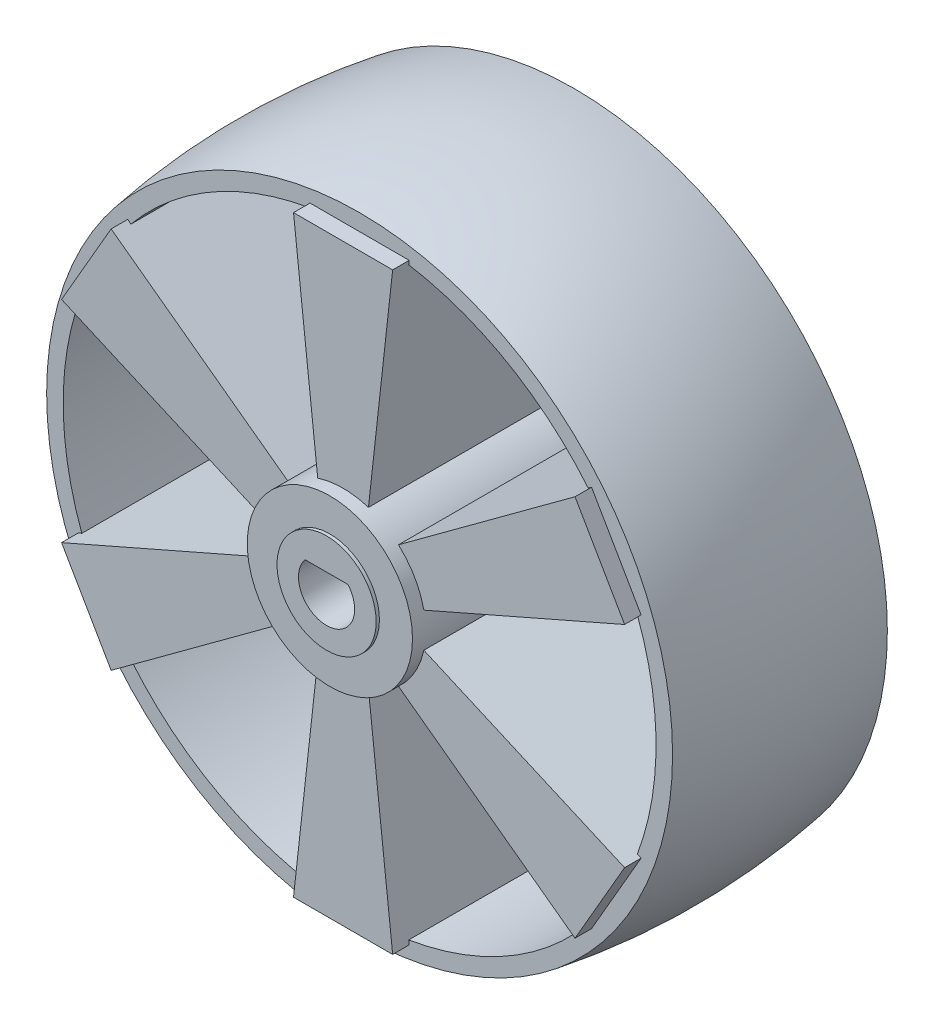
SolidWorks part; units mm, degrees
ref_plane "Alzado" through (0, 0, 0) normal (0, 0, 1) x (1, 0, 0)
ref_plane "Planta" through (0, 0, 0) normal (0, 1, 0) x (1, 0, 0)
ref_plane "Vista lateral" through (0, 0, 0) normal (1, 0, 0) x (0, 0, -1)
sketch "Croquis1" plane through (0, 0, 0) normal (0, 0, 1) x (1, 0, 0)
  line L0 (-1.2961, 1.1) -> (1.2961, 1.1)
  line L2 (0, -1.7) -> (0.7656, -1.7) construction
  line L3 (0, -1.7) -> (-1.151, -1.7) construction
  circle A1 centre (0, 0) radius 3
  arc A2 (-1.2961, 1.1) -> (1.2961, 1.1) centre (0, 0) ccw
  dimension "D1" = 3.4
  dimension "D3" = 6
  dimension "D2" = 2.8
extrude "Saliente-Extruir1" add sketch "Croquis1" along normal blind 5
sketch "Croquis2" plane through (0, 0, 0) normal (0, 0, -1) x (-1, 0, 0)
  circle A0 centre (0, 0) radius 5.0005
extrude "Saliente-Extruir2" add sketch "Croquis2" along normal blind 10
sketch "Croquis3" plane through (0, 0, 0) normal (0, 0, 1) x (1, 0, 0)
  circle A0 centre (0, 0) radius 3
  circle A1 centre (0, 0) radius 5.0005
extrude "Saliente-Extruir3" add sketch "Croquis3" along normal blind 4.8
sketch "Croquis4" plane through (0, 0, -10) normal (0, 0, -1) x (-1, 0, 0)
  line L0 (0, 4.442) -> (-1.5, 4.442)
  line L1 (-1.5, 4.442) -> (-3, 17.942)
  line L3 (3, 17.942) -> (1.5, 4.442)
  line L4 (1.5, 4.442) -> (0, 4.442)
  line L5 (-3, 17.942) -> (0, 17.942)
  line L6 (0, 17.942) -> (3, 17.942)
  line L8 (15.5383, 8.971) -> (17.0383, 6.3729)
  line L9 (17.0383, 6.3729) -> (4.5969, 0.922)
  line L10 (4.5969, 0.922) -> (3.8469, 2.221)
  line L11 (3.8469, 2.221) -> (3.0969, 3.5201)
  line L12 (3.0969, 3.5201) -> (14.0383, 11.5691)
  line L13 (14.0383, 11.5691) -> (15.5383, 8.971)
  line L14 (15.5383, -8.971) -> (14.0383, -11.5691)
  line L15 (14.0383, -11.5691) -> (3.0969, -3.5201)
  line L16 (3.0969, -3.5201) -> (3.8469, -2.221)
  line L17 (3.8469, -2.221) -> (4.5969, -0.922)
  line L18 (4.5969, -0.922) -> (17.0383, -6.3729)
  line L19 (17.0383, -6.3729) -> (15.5383, -8.971)
  line L20 (0, -17.942) -> (-3, -17.942)
  line L21 (-3, -17.942) -> (-1.5, -4.442)
  line L22 (-1.5, -4.442) -> (0, -4.442)
  line L23 (0, -4.442) -> (1.5, -4.442)
  line L24 (1.5, -4.442) -> (3, -17.942)
  line L25 (3, -17.942) -> (0, -17.942)
  line L26 (-15.5383, -8.971) -> (-17.0383, -6.3729)
  line L27 (-17.0383, -6.3729) -> (-4.5969, -0.922)
  line L28 (-4.5969, -0.922) -> (-3.8469, -2.221)
  line L29 (-3.8469, -2.221) -> (-3.0969, -3.5201)
  line L30 (-3.0969, -3.5201) -> (-14.0383, -11.5691)
  line L31 (-14.0383, -11.5691) -> (-15.5383, -8.971)
  line L32 (-15.5383, 8.971) -> (-14.0383, 11.5691)
  line L33 (-14.0383, 11.5691) -> (-3.0969, 3.5201)
  line L34 (-3.0969, 3.5201) -> (-3.8469, 2.221)
  line L35 (-3.8469, 2.221) -> (-4.5969, 0.922)
  line L36 (-4.5969, 0.922) -> (-17.0383, 6.3729)
  line L37 (-17.0383, 6.3729) -> (-15.5383, 8.971)
  circle A0 centre (0, 0) radius 17.5 construction
  point P44 (0, 0)
  dimension "D1" = 35
  dimension "D2" = 1.5
  dimension "D3" = 1.5
  dimension "D4" = 3
  dimension "D5" = 3
  dimension "D6" = 6
extrude "Saliente-Extruir4" add sketch "Croquis4" against normal blind 14
sketch "Croquis5" plane through (0, 0, -10) normal (0, 0, -1) x (-1, 0, 0)
  circle A0 centre (0, 0) radius 17.942
  dimension "D1" = 35.8841
sketch "Croquis6" plane through (0, 0, 0) normal (1, 0, 0) x (0, 0, -1)
  line L12 (10, 17.942) -> (10, 18.942)
  line L13 (-4, 0) -> (10, 0) construction
  line L14 (10, -17.942) -> (10, 17.942) construction
  line L15 (10, 17.942) -> (-3, 17.942)
  line L16 (-4, 17.942) -> (10, 17.942) construction
  line L17 (-3, 17.942) -> (-3, 18.942)
  line L19 (-3, 17.942) -> (-4, 17.942) construction
  arc A1 (-3, 18.942) -> (10, 18.942) centre (3.5, -20.5263) cw
  dimension "D4" = 1
  dimension "D5" = 40
  dimension "D1" = 13
  dimension "D2" = 1
  dimension "D3" = 17.942
  dimension "D6" = 1
  dimension "D7" = 18.942
revolve "Revolución2" add sketch "Croquis6" angle 360 about L13
